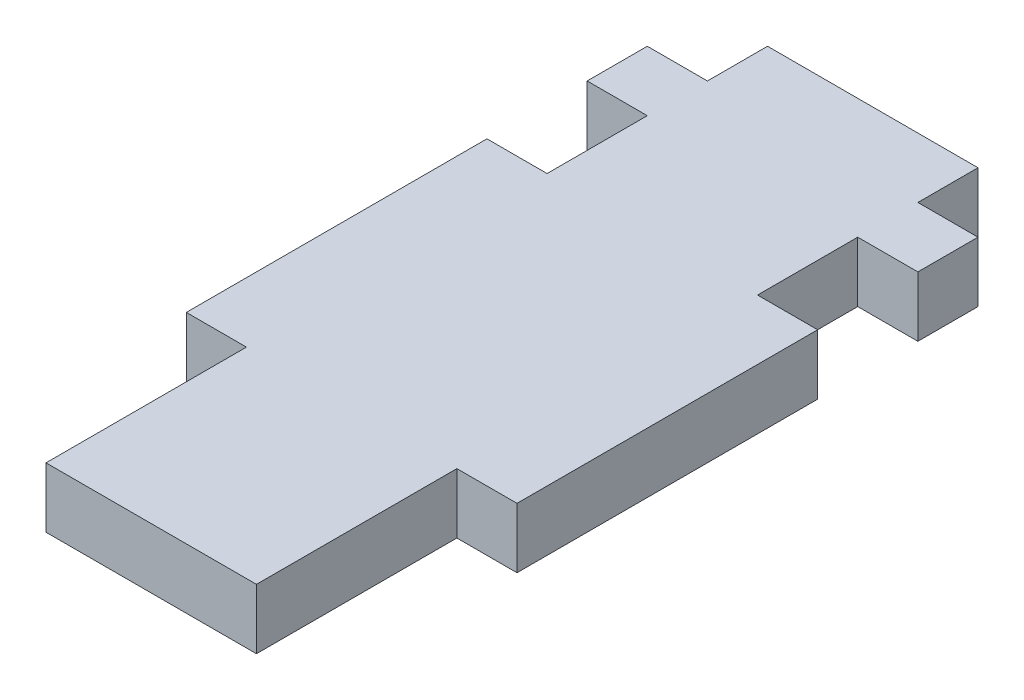
SolidWorks part; units mm, degrees
ref_plane "前视基准面" through (0, 0, 0) normal (0, 0, 1) x (1, 0, 0)
ref_plane "上视基准面" through (0, 0, 0) normal (0, 1, 0) x (1, 0, 0)
ref_plane "右视基准面" through (0, 0, 0) normal (1, 0, 0) x (0, 0, -1)
other "Configuration Table"
sketch "草图1" plane through (0, 0, 0) normal (0, 1, 0) x (1, 0, 0)
  line L0 (8.25, 0) -> (8.25, -30)
  line L1 (0, 0) -> (16.5, 0)
  line L2 (0, 0) -> (0, -30)
  line L3 (0, -30) -> (16.5, -30)
  line L4 (16.5, 0) -> (16.5, -30)
  line L21 (16.5, -20) -> (13.5, -20)
  line L22 (0, -30) -> (3, -30)
  line L23 (0, -30) -> (0, -20)
  line L24 (0, -20) -> (3, -20)
  line L25 (3, -30) -> (3, -20)
  line L26 (0, 0) -> (3, 0)
  line L27 (0, 0) -> (0, -5)
  line L28 (0, -5) -> (3, -5)
  line L29 (3, 0) -> (3, -5)
  line L30 (13.5, -30) -> (13.5, -20)
  line L31 (16.5, -30) -> (13.5, -30)
  line L32 (16.5, -30) -> (16.5, -20)
  line L33 (16.5, -5) -> (13.5, -5)
  line L34 (13.5, 0) -> (13.5, -5)
  line L35 (16.5, 0) -> (13.5, 0)
  line L36 (16.5, 0) -> (16.5, -5)
  line L38 (0, 0) -> (16.5, 0)
  line L39 (0, 0) -> (0, 3)
  line L40 (0, 3) -> (16.5, 3)
  line L41 (16.5, 0) -> (16.5, 3)
  line L42 (3, 3) -> (13.5, 3)
  line L43 (3, 3) -> (3, 6)
  line L44 (3, 6) -> (13.5, 6)
  line L45 (13.5, 3) -> (13.5, 6)
  dimension "D1" = 16.5
  dimension "D2" = 30
  dimension "D3" = 3
  dimension "D4" = 10
  dimension "D5" = 5
  dimension "D6" = 3
  dimension "D7" = 3
extrude "凸台-拉伸1" add sketch "草图1" along normal blind 3 contours L2 L3 L0 L1 | L4 L1 L0 L3 | L1 L41 L40 L39 | L40 L45 L44 L43
